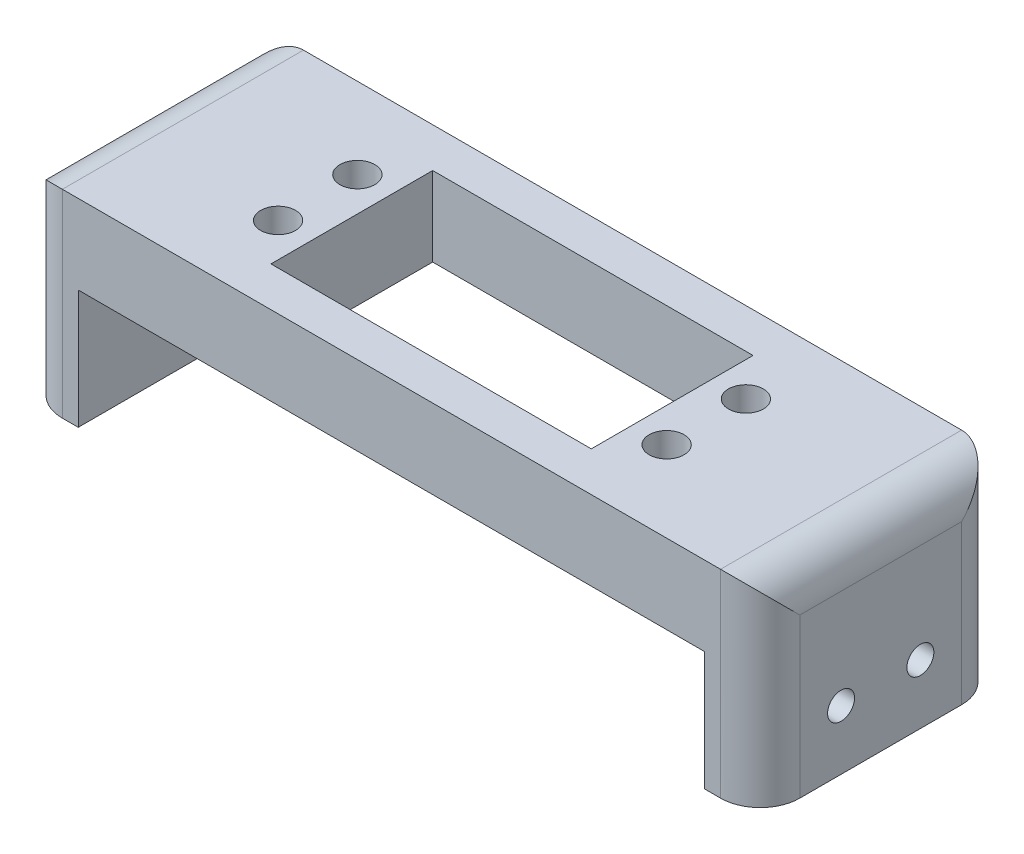
SolidWorks part; units mm, degrees
ref_plane "前视基准面" through (0, 0, 0) normal (0, 0, 1) x (1, 0, 0)
ref_plane "上视基准面" through (0, 0, 0) normal (0, 1, 0) x (1, 0, 0)
ref_plane "右视基准面" through (0, 0, 0) normal (1, 0, 0) x (0, 0, -1)
sketch "草图1" plane through (0, 0, 0) normal (0, 1, 0) x (1, 0, 0)
  line L0 (0, 10.2) -> (0, 15.2) construction
  line L1 (-20.2, -10.2) -> (20.2, -10.2)
  line L2 (-20.2, -10.2) -> (-20.2, 10.2)
  line L3 (-20.2, 10.2) -> (20.2, 10.2)
  line L4 (20.2, -10.2) -> (20.2, 10.2)
  line L5 (-20.2, -10.2) -> (20.2, 10.2) construction
  line L6 (-20.2, 10.2) -> (20.2, -10.2) construction
  line L7 (-24.5, -5) -> (24.5, -5) construction
  line L8 (-24.5, -5) -> (-24.5, 5) construction
  line L9 (-24.5, 5) -> (24.5, 5) construction
  line L10 (24.5, -5) -> (24.5, 5) construction
  line L11 (-24.5, -5) -> (24.5, 5) construction
  line L12 (-24.5, 5) -> (24.5, -5) construction
  line L13 (-46.5, 15.2) -> (46.5, 15.2)
  line L14 (-46.5, 15.2) -> (-46.5, -15.2)
  line L15 (-46.5, -15.2) -> (46.5, -15.2)
  line L16 (46.5, 15.2) -> (46.5, -15.2)
  line L17 (0, -10.2) -> (0, -15.2) construction
  line L18 (-46.5, 0) -> (-39, 0) construction
  line L19 (-39, 0) -> (39, 0) construction
  line L20 (39, 0) -> (46.5, 0) construction
  circle A0 centre (-24.5, 5) radius 2.2
  circle A1 centre (-24.5, -5) radius 2.2
  circle A2 centre (24.5, -5) radius 2.2
  circle A3 centre (24.5, 5) radius 2.2
  point P0 (0, 0)
  point P6 (0, 0)
  point P15 (0, 0)
  dimension "D3" = 4.4
  dimension "D1" = 40.4
  dimension "D2" = 20.4
  dimension "D4" = 10
  dimension "D5" = 49
  dimension "D6" = 5
  dimension "D7" = 93
  dimension "D8" = 78
extrude "凸台-拉伸1" add sketch "草图1" along normal blind 10
sketch "草图2" plane through (0, 0, 0) normal (0, -1, 0) x (1, 0, 0)
  line L5 (-46.5, 15.2) -> (46.5, 15.2) construction
  line L10 (-46.5, -15.2) -> (-39.5, -15.2)
  line L11 (-46.5, -15.2) -> (-46.5, 15.2)
  line L12 (-46.5, 15.2) -> (-39.5, 15.2)
  line L13 (-39.5, -15.2) -> (-39.5, 15.2)
  line L14 (46.5, -15.2) -> (-46.5, -15.2) construction
  line L15 (46.5, 15.2) -> (39.5, 15.2)
  line L16 (46.5, 15.2) -> (46.5, -15.2)
  line L17 (46.5, -15.2) -> (39.5, -15.2)
  line L18 (39.5, 15.2) -> (39.5, -15.2)
  dimension "D1" = 7
extrude "凸台-拉伸2" add sketch "草图2" along normal blind 15
sketch "草图4" plane through (-46.5, 0, 0) normal (-1, 0, 0) x (0, 0, 1)
  line L0 (-15.2, -7.5) -> (-5, -7.5) construction
  line L3 (-15.2, 10) -> (-15.2, -15) construction
  line L4 (-5, -7.5) -> (5, -7.5) construction
  line L5 (5, -7.5) -> (15.2, -7.5) construction
  line L6 (15.2, 10) -> (15.2, -15) construction
  line L7 (15.2, -15) -> (-15.2, -15) construction
  circle A0 centre (-5, -7.5) radius 1.7
  circle A1 centre (5, -7.5) radius 1.7
  dimension "D3" = 3.4
  dimension "D1" = 7.5
  dimension "D2" = 10
extrude "切除-拉伸2" cut sketch "草图4" against normal through all
fillet "圆角1" radius 5 6 edges at (46.5, 10, 0) (46.5, -2.5, 15.2) (46.5, -2.5, -15.2) (-46.5, 10, 0) (-46.5, -2.5, -15.2) (-46.5, -2.5, 15.2)
